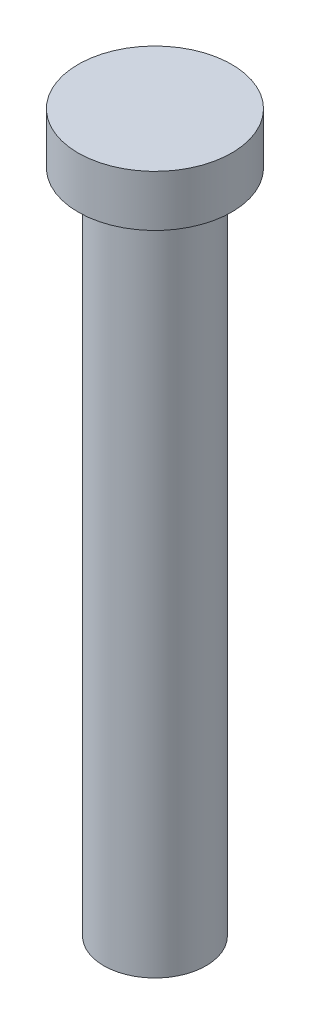
SolidWorks part; units mm, degrees
ref_plane "정면" through (0, 0, 0) normal (0, 0, 1) x (1, 0, 0)
ref_plane "윗면" through (0, 0, 0) normal (0, 1, 0) x (1, 0, 0)
ref_plane "우측면" through (0, 0, 0) normal (1, 0, 0) x (0, 0, -1)
sketch "스케치1" plane through (0, 0, 0) normal (1, 0, 0) x (0, 0, -1)
  line L0 (0, 20.9905) -> (0, -20.0677) construction
  line L1 (0, 16.2462) -> (3, 16.2462)
  line L2 (3, 16.2462) -> (3, 14.2462)
  line L3 (3, 14.2462) -> (2, 14.2462)
  line L4 (2, 14.2462) -> (2, -11.7538)
  line L5 (2, -11.7538) -> (0, -11.7538)
  line L6 (0, 16.2462) -> (0, -11.7538)
  dimension "D1" = 26
  dimension "D2" = 2
  dimension "D3" = 3
  dimension "D4" = 2
revolve "회전1" add sketch "스케치1" angle 360 about L0
